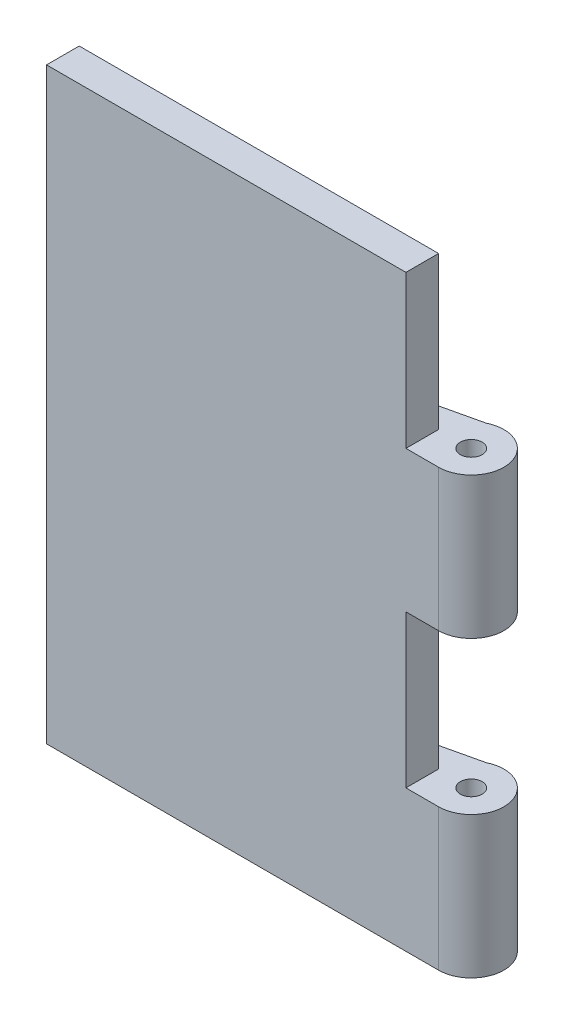
SolidWorks part; units mm, degrees
ref_plane "Front Plane" through (0, 0, 0) normal (0, 0, 1) x (1, 0, 0)
ref_plane "Top Plane" through (0, 0, 0) normal (0, 1, 0) x (1, 0, 0)
ref_plane "Right Plane" through (0, 0, 0) normal (1, 0, 0) x (0, 0, -1)
sketch "Sketch1" plane through (0, 0, 0) normal (0, 1, 0) x (1, 0, 0)
  line L0 (7.5, 0.75) -> (9, 0.75) construction
  line L1 (7.5, -0.75) -> (-7.5, -0.75)
  line L2 (7.5, -0.75) -> (7.5, 0.75)
  line L3 (7.5, 0.75) -> (-7.5, 0.75)
  line L4 (-7.5, -0.75) -> (-7.5, 0.75)
  line L5 (7.5, -0.75) -> (-7.5, 0.75) construction
  line L6 (7.5, 0.75) -> (-7.5, -0.75) construction
  line L7 (7.5, -0.75) -> (9, -0.75)
  line L8 (0, 0.75) -> (2.5, 0.75) construction
  line L9 (9, 2.25) -> (2.5, 0.75)
  circle A0 centre (9, 0.75) radius 1.5
  point P0 (0, 0)
  dimension "D1" = 15
  dimension "D2" = 1.5
  dimension "D3" = 1.5
extrude "Boss-Extrude1" add sketch "Sketch1" along normal blind 6.5 contours A0 L9 L3 | L4 L1 L2 L3 | A0 L2 L7
sketch "Sketch2" plane through (0, 6.5, 0) normal (0, 1, 0) x (1, 0, 0)
  line L1 (7.5, -0.75) -> (-7.5, -0.75)
  line L2 (7.5, -0.75) -> (7.5, 0.75)
  line L3 (7.5, 0.75) -> (-7.5, 0.75)
  line L4 (-7.5, -0.75) -> (-7.5, 0.75)
  line L5 (7.5, -0.75) -> (-7.5, 0.75) construction
  line L6 (7.5, 0.75) -> (-7.5, -0.75) construction
  point P0 (0, 0)
  point P6 (0, 0)
extrude "Boss-Extrude2" add sketch "Sketch2" along normal blind 7
sketch "Sketch3" plane through (0, 13.5, 0) normal (0, 1, 0) x (1, 0, 0)
  line L0 (7.5, 0.75) -> (9, 0.75) construction
  line L1 (7.5, -0.75) -> (-7.5, -0.75)
  line L2 (7.5, -0.75) -> (7.5, 0.75)
  line L3 (7.5, 0.75) -> (-7.5, 0.75)
  line L4 (-7.5, -0.75) -> (-7.5, 0.75)
  line L5 (7.5, -0.75) -> (-7.5, 0.75) construction
  line L6 (7.5, 0.75) -> (-7.5, -0.75) construction
  line L7 (7.5, -0.75) -> (9, -0.75)
  line L8 (0, 0.75) -> (2.5, 0.75)
  line L9 (2.5, 0.75) -> (9, 2.25)
  circle A0 centre (9, 0.75) radius 1.5
  point P0 (0, 0)
  line M2 (-7.5, 0.75) -> (-7.5, -0.75)
  line M3 (-7.5, -0.75) -> (7.5, -0.75)
  line M4 (7.5, -0.75) -> (7.5, 0.75)
  line M5 (7.5, 0.75) -> (-7.5, 0.75)
extrude "Boss-Extrude3" add sketch "Sketch3" along normal blind 6.5 contours L3 M5 M2 M3 M4 | L2 L3 L1 M4 | A0 L2 L7 | A0 L9 L3 M5 | A0 L9
sketch "Sketch4" plane through (0, 20, 0) normal (0, 1, 0) x (1, 0, 0)
  line L1 (7.5, -0.75) -> (-7.5, -0.75)
  line L2 (7.5, -0.75) -> (7.5, 0.75)
  line L3 (7.5, 0.75) -> (-7.5, 0.75)
  line L4 (-7.5, -0.75) -> (-7.5, 0.75)
  line L5 (7.5, -0.75) -> (-7.5, 0.75) construction
  line L6 (7.5, 0.75) -> (-7.5, -0.75) construction
  point P0 (0, 0)
extrude "Boss-Extrude4" add sketch "Sketch4" along normal blind 7
sketch "Sketch5" plane through (0, 0, 0) normal (0, -1, 0) x (1, 0, 0)
  line L0 (-7.5, -0.75) -> (9, -0.75) construction
  circle A0 centre (9, -0.75) radius 0.5
extrude "Cut-Extrude1" cut sketch "Sketch5" against normal blind 27
sketch "Sketch6" plane through (-7.5, 0, 0) normal (-1, 0, 0) x (0, 0, 1)
  line L1 (-0.75, 27) -> (0.75, 27)
  line L2 (-0.75, 27) -> (-0.75, 0)
  line L3 (-0.75, 0) -> (0.75, 0)
  line L4 (0.75, 27) -> (0.75, 0)
extrude "Boss-Extrude5" add sketch "Sketch6" along normal blind 1.5
